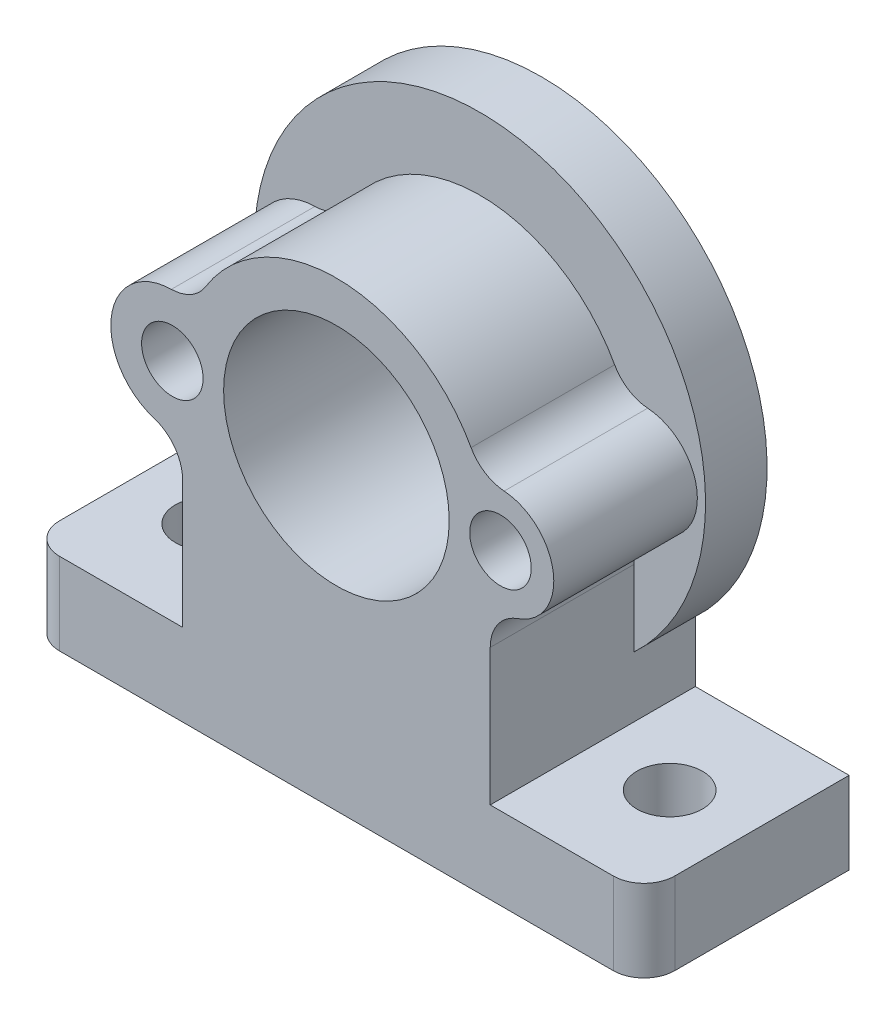
SolidWorks part; units mm, degrees
ref_plane "Front Plane" through (0, 0, 0) normal (0, 0, 1) x (1, 0, 0)
ref_plane "Top Plane" through (0, 0, 0) normal (0, 1, 0) x (1, 0, 0)
ref_plane "Right Plane" through (0, 0, 0) normal (1, 0, 0) x (0, 0, -1)
sketch "Sketch1" plane through (0, 0, 0) normal (0, 0, 1) x (1, 0, 0)
  line L0 (0, 7.5) -> (0, -11.0753) construction
  line L2 (7.5, -15) -> (-7.5, -15)
  line L3 (7.5, -15) -> (7.5, 0)
  line L4 (7.5, 0) -> (-7.5, 0)
  line L5 (-7.5, -15) -> (-7.5, 0)
  line L6 (7.5, -15) -> (-7.5, 0) construction
  line L7 (7.5, 0) -> (-7.5, -15) construction
  line L8 (-15, -11) -> (15, -11)
  line L9 (-15, -11) -> (-15, -15)
  line L10 (-15, -15) -> (15, -15)
  line L11 (15, -11) -> (15, -15)
  line L12 (-15, -11) -> (15, -15) construction
  line L13 (-15, -15) -> (15, -11) construction
  circle A0 centre (0, 0) radius 7.5
  circle A1 centre (0, 0) radius 5.5
  point P5 (0, -7.5)
  point P11 (0, -13)
  dimension "D2" = 2
  dimension "D3" = 11
  dimension "D1" = 15
  dimension "D4" = 4
  dimension "D5" = 30
extrude "Boss-Extrude1" add sketch "Sketch1" along normal blind 10 contours L11 L8 L3 L10 | L8 L5 L2 L3 | A0 L5 L8 L3 | L9 L10 L5 L8 | A1 L4 A0 | A1 L4 A0
sketch "Sketch2" plane through (0, -11, 0) normal (0, 1, 0) x (1, 0, 0)
  line L0 (15, -5) -> (7.5, -5) construction
  line L1 (15, -10) -> (15, 0) construction
  line L2 (7.5, -10) -> (7.5, 0) construction
  line L3 (-15, -5) -> (-7.5, -5) construction
  line L4 (-15, -10) -> (-15, 0) construction
  line L5 (-7.5, -10) -> (-7.5, 0) construction
  circle A0 centre (-11.25, -5) radius 1.6
  circle A1 centre (11.25, -5) radius 1.6
  dimension "D1" = 3.2
  dimension "D2" = 3.2
extrude "Cut-Extrude1" cut sketch "Sketch2" against normal through all
sketch "Sketch3" plane through (0, 0, 0) normal (0, 0, -1) x (-1, 0, 0)
  circle A0 centre (0, 0) radius 5.5
  circle A1 centre (0, 0) radius 11
  dimension "D1" = 22
  dimension "D2" = 11
extrude "Boss-Extrude2" add sketch "Sketch3" against normal blind 3
sketch "Sketch4" plane through (0, 0, 0) normal (0, 0, -1) x (-1, 0, 0)
  line L0 (-11, 0) -> (11, 0) construction
  line L1 (0, 11) -> (0, -15) construction
  line L2 (15, -15) -> (-15, -15) construction
  arc A0 (7.5, -8.0467) -> (-7.5, -8.0467) centre (0, 0) ccw construction
  circle A1 centre (8, 0) radius 1.5
  circle A2 centre (-8, 0) radius 1.5
  dimension "D1" = 3
  dimension "D2" = 16
extrude "Cut-Extrude2" cut sketch "Sketch4" against normal through all
sketch "Sketch5" plane through (0, 0, 10) normal (0, 0, 1) x (1, 0, 0)
  circle A0 centre (8, 0) radius 2.6
  circle A1 centre (-8, 0) radius 3
  circle A2 centre (-8, 0) radius 1.5
  circle A3 centre (8, 0) radius 1.5
  circle A4 centre (0, 0) radius 5.5
  arc M2 (7.375, 1.3636) -> (-7.375, 1.3636) centre (0, 0) ccw
  line M4 (-7.5, -1.4142) -> (-7.5, -11)
  line M10 (7.5, -11) -> (7.5, -1.4142)
  dimension "D1" = 6
  dimension "D2" = 5.2
extrude "Boss-Extrude3" add sketch "Sketch5" against normal through all contours A2 A1 M2 M4 | A3 A0 M10 M2
fillet "Fillet1" radius 2 4 edges at (-7.5, -2.958, 6.5) (7.5, -2.5515, 6.5) (7.0931, 2.4367, 6.5) (-6.9531, 2.8114, 6.5)
fillet "Fillet2" radius 1.5 2 edges at (15, -13, 10) (-15, -13, 10)
